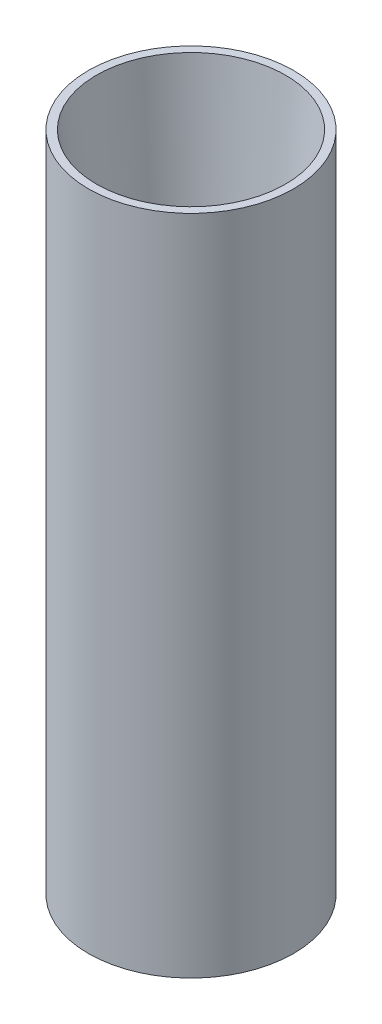
SolidWorks part; units mm, degrees
material "Brass"
ref_plane "Front Plane" through (0, 0, 0) normal (0, 0, 1) x (1, 0, 0)
ref_plane "Top Plane" through (0, 0, 0) normal (0, 1, 0) x (1, 0, 0)
ref_plane "Right Plane" through (0, 0, 0) normal (1, 0, 0) x (0, 0, -1)
sketch "Sketch1" plane through (0, 0, 0) normal (0, 1, 0) x (1, 0, 0)
  circle A0 centre (0, 0) radius 12.7
  dimension "D1" = 25.4
extrude "Boss-Extrude1" add sketch "Sketch1" against normal blind 82
sketch "Sketch2" plane through (0, 0, 0) normal (0, 1, 0) x (1, 0, 0)
  circle A0 centre (0, 0) radius 11.7
  dimension "D1" = 23.4
extrude "Cut-Extrude1" cut sketch "Sketch2" against normal blind 25.4 draft 5
sketch "Sketch3" plane through (0, -25.4, 0) normal (0, 1, 0) x (1, 0, 0)
  circle A0 centre (0, 0) radius 10.7
  dimension "D1" = 21.4
extrude "Cut-Extrude2" cut sketch "Sketch3" against normal blind 53.38
sketch "Sketch4" plane through (0, -78.78, 0) normal (0, 1, 0) x (1, 0, 0)
  circle A0 centre (0, 0) radius 11.2
  dimension "D1" = 22.4
extrude "Cut-Extrude3" cut sketch "Sketch4" against normal through all
